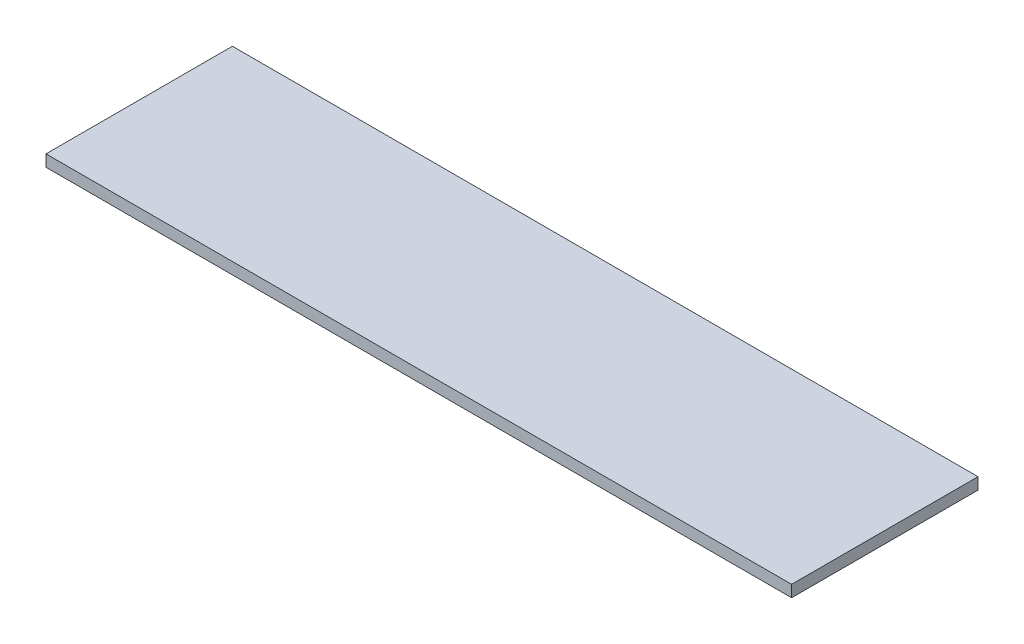
SolidWorks part; units mm, degrees
material "Nylon 101"
ref_plane "Front Plane" through (0, 0, 0) normal (0, 0, 1) x (1, 0, 0)
ref_plane "Top Plane" through (0, 0, 0) normal (0, 1, 0) x (1, 0, 0)
ref_plane "Right Plane" through (0, 0, 0) normal (1, 0, 0) x (0, 0, -1)
sketch "Sketch2" plane through (0, 0, 0) normal (0, 1, 0) x (1, 0, 0)
  line L1 (0, 0) -> (101.6, 0)
  line L2 (0, 0) -> (0, 25.4)
  line L3 (0, 25.4) -> (101.6, 25.4)
  line L4 (101.6, 0) -> (101.6, 25.4)
  dimension "D1" = 25.4
  dimension "D2" = 101.6
extrude "Boss-Extrude1" add sketch "Sketch2" along normal blind 1.5875
